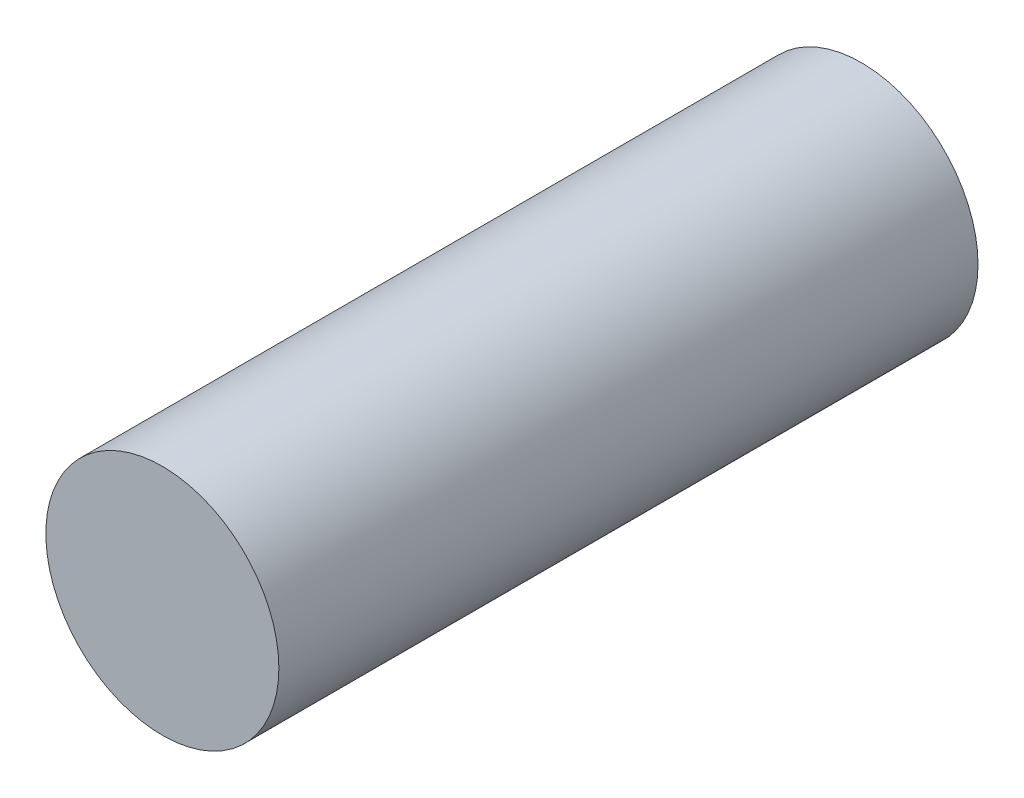
SolidWorks part; units mm, degrees
ref_plane "前视基准面" through (0, 0, 0) normal (0, 0, 1) x (1, 0, 0)
ref_plane "上视基准面" through (0, 0, 0) normal (0, 1, 0) x (1, 0, 0)
ref_plane "右视基准面" through (0, 0, 0) normal (1, 0, 0) x (0, 0, -1)
sketch "草图1" plane through (0, 0, 0) normal (0, 0, 1) x (1, 0, 0)
  circle A0 centre (0, 0) radius 25
  dimension "D1" = 50
extrude "凸台-拉伸1" add sketch "草图1" along normal blind 150
sketch "草图2" plane through (0, 0, 0) normal (0, 0, -1) x (-1, 0, 0)
  line L1 (3.7943, 7.393) -> (6.8453, 7.393)
  line L2 (3.7943, 7.393) -> (3.7943, -9.1923)
  line L3 (3.7943, -9.1923) -> (6.8453, -9.1923)
  line L4 (6.8453, 7.393) -> (6.8453, -9.1923)
extrude "切除-拉伸1" cut sketch "草图2" against normal blind 6
